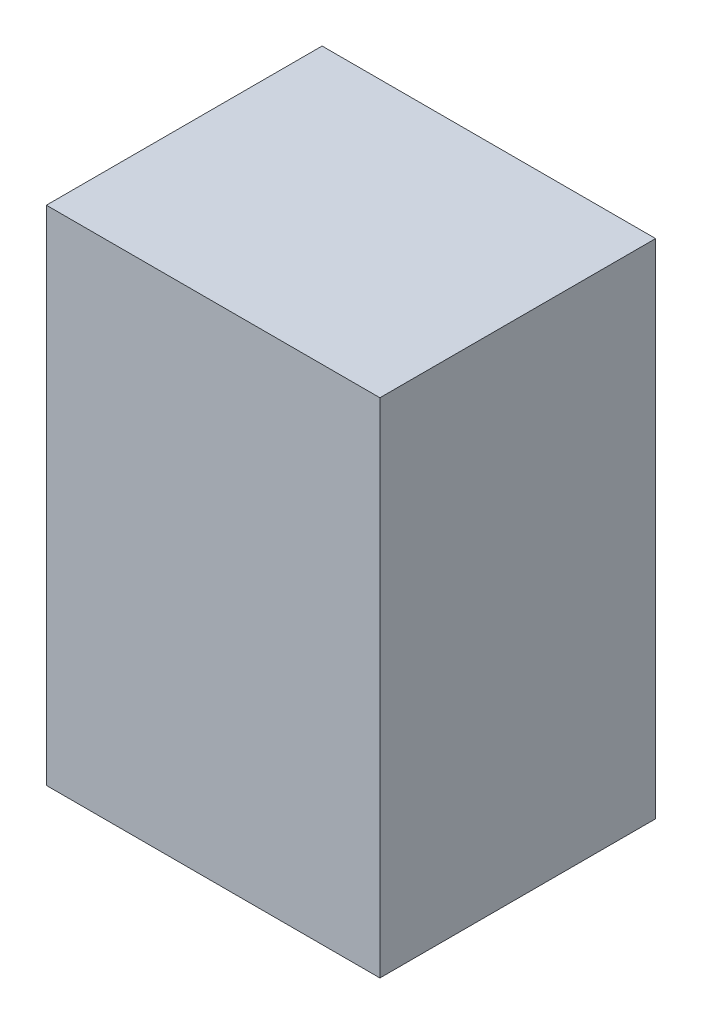
SolidWorks part; units mm, degrees
ref_plane "Ebene vorne" through (0, 0, 0) normal (1, 0, 0) x (0, 1, 0)
ref_plane "Ebene oben" through (0, 0, 0) normal (0, 0, 1) x (0, 1, 0)
ref_plane "Ebene rechts" through (0, 0, 0) normal (0, 1, 0) x (-1, 0, 0)
sketch "Skizze1" plane through (0, 0, 0) normal (0, 0, 1) x (0, 1, 0)
  line L1 (-56.5, 37.5) -> (56.5, 37.5)
  line L2 (-56.5, 37.5) -> (-56.5, -37.5)
  line L3 (-56.5, -37.5) -> (56.5, -37.5)
  line L4 (56.5, 37.5) -> (56.5, -37.5)
  line L5 (-56.5, 37.5) -> (56.5, -37.5) construction
  line L6 (-56.5, -37.5) -> (56.5, 37.5) construction
  point P0 (0, 0)
  dimension "D1" = 75
  dimension "D2" = 113
extrude "Aufsatz-Linear austragen1" add sketch "Skizze1" along normal blind 62
